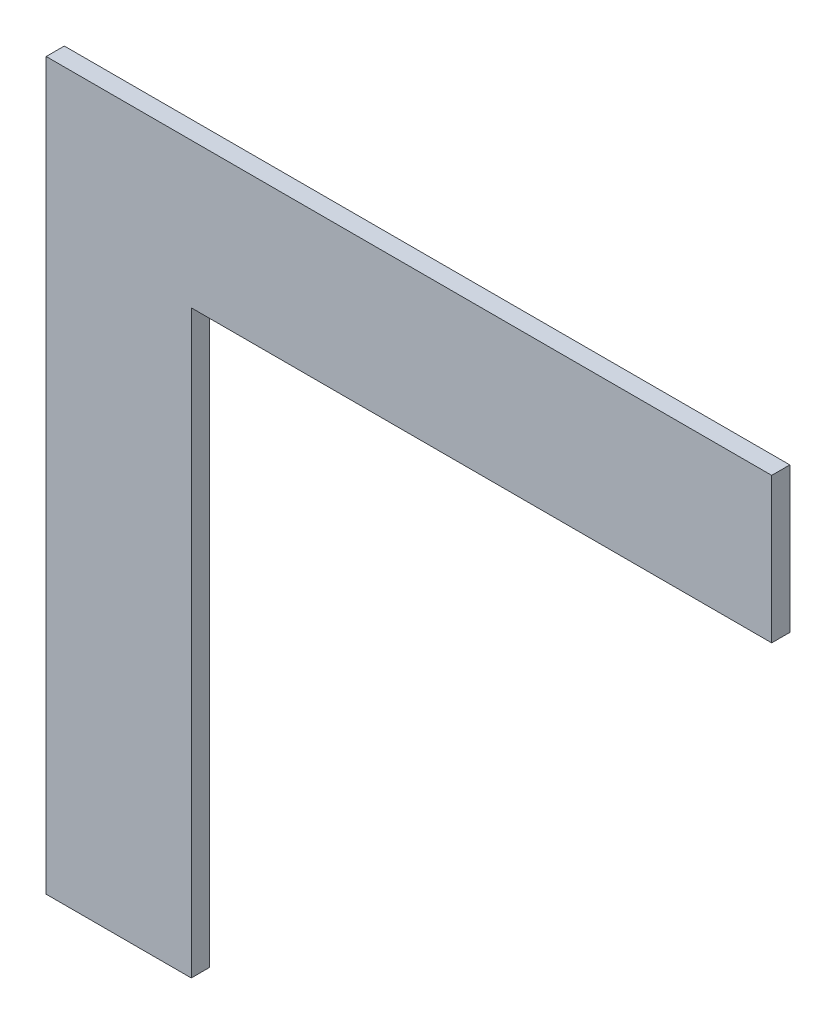
SolidWorks part; units mm, degrees
ref_plane "Front Plane" through (0, 0, 0) normal (0, 0, 1) x (1, 0, 0)
ref_plane "Top Plane" through (0, 0, 0) normal (0, 1, 0) x (1, 0, 0)
ref_plane "Right Plane" through (0, 0, 0) normal (1, 0, 0) x (0, 0, -1)
sketch "Sketch1" plane through (0, 0, 0) normal (0, 0, 1) x (1, 0, 0)
  line L0 (0, 0) -> (0, 203.2)
  line L1 (0, 203.2) -> (203.2, 203.2)
  line L2 (203.2, 203.2) -> (203.2, 254)
  line L3 (203.2, 254) -> (-50.8, 254)
  line L4 (-50.8, 254) -> (-50.8, 0)
  line L5 (-50.8, 0) -> (0, 0)
  dimension "D1" = 254
  dimension "D2" = 254
  dimension "D3" = 50.8
  dimension "D4" = 50.8
extrude "Boss-Extrude1" add sketch "Sketch1" along normal blind 6.35
